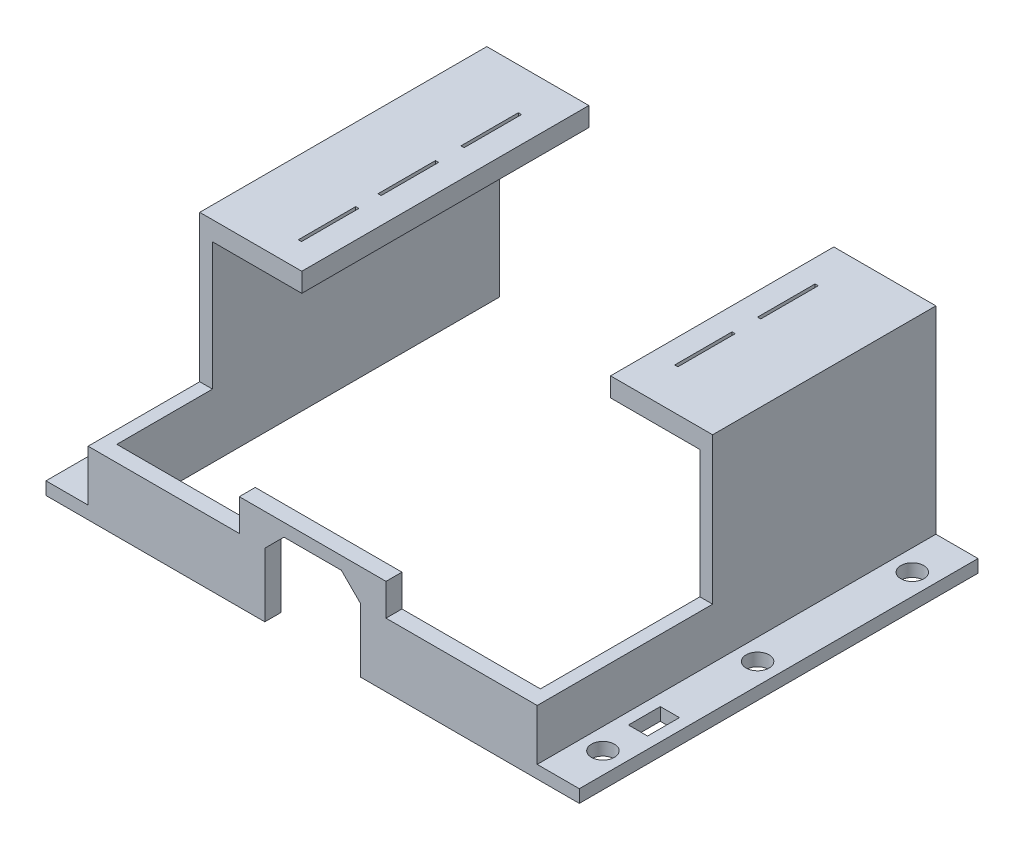
SolidWorks part; units mm, degrees
ref_plane "前视基准面" through (0, 0, 0) normal (0, 0, 1) x (1, 0, 0)
ref_plane "上视基准面" through (0, 0, 0) normal (0, 1, 0) x (1, 0, 0)
ref_plane "右视基准面" through (0, 0, 0) normal (1, 0, 0) x (0, 0, -1)
sketch "Sketch1" plane through (0, 0, 0) normal (0, 1, 0) x (1, 0, 0)
  line L1 (0, 0) -> (70.4, 0)
  line L2 (0, 0) -> (0, 2)
  line L3 (0, 2) -> (70.4, 2)
  line L4 (70.4, 0) -> (70.4, 2)
  dimension "D1" = 70.4
  dimension "D2" = 2
extrude "Boss-Extrude2" add sketch "Sketch1" along normal blind 10
sketch "Sketch2" plane through (0, 10, 0) normal (0, 1, 0) x (1, 0, 0)
  line L1 (0, 2) -> (2, 2)
  line L2 (0, 2) -> (0, 57)
  line L3 (0, 57) -> (2, 57)
  line L4 (2, 2) -> (2, 57)
  line L5 (70.4, 2) -> (68.4, 2)
  line L6 (70.4, 2) -> (70.4, 57)
  line L7 (70.4, 57) -> (68.4, 57)
  line L8 (68.4, 2) -> (68.4, 57)
  dimension "D1" = 55
  dimension "D2" = 2
  dimension "D3" = 2
extrude "Boss-Extrude3" add sketch "Sketch2" against normal blind 10
sketch "Sketch3" plane through (0, 0, 0) normal (0, 0, 1) x (1, 0, 0)
  line L0 (35.2, 0) -> (35.2, 21.6902) construction
  line L1 (0, 0) -> (70.4, 0) construction
  line L2 (0, 10) -> (70.4, 10) construction
  line L3 (25.7, 10) -> (44.7, 10)
  line L4 (25.7, 10) -> (25.7, 13)
  line L5 (25.7, 13) -> (44.7, 13)
  line L6 (44.7, 10) -> (44.7, 13)
  dimension "D1" = 9.5
  dimension "D2" = 9.5
  dimension "D3" = 3
extrude "Boss-Extrude4" add sketch "Sketch3" against normal blind 2
sketch "Sketch4" plane through (0, 0, 0) normal (0, 0, 1) x (1, 0, 0)
  line L0 (35.2, 0) -> (35.2, 21.4055) construction
  line L1 (0, 0) -> (70.4, 0) construction
  line L3 (27.7, 0) -> (42.7, 0)
  line L4 (27.7, 0) -> (27.7, 10)
  line L5 (27.7, 10) -> (42.7, 10)
  line L6 (42.7, 0) -> (42.7, 10)
  dimension "D1" = 10
  dimension "D2" = 7.5
  dimension "D3" = 7.5
extrude "Cut-Extrude2" cut sketch "Sketch4" against normal blind 2
sketch "Sketch5" plane through (25.7, 0, 0) normal (-1, 0, 0) x (0, 0, 1)
  line L1 (-2, 13) -> (0, 13)
  line L2 (-2, 13) -> (-2, 10)
  line L3 (-2, 10) -> (0, 10)
  line L4 (0, 13) -> (0, 10)
extrude "Boss-Extrude5" add sketch "Sketch5" along normal blind 1
sketch "Sketch6" plane through (44.7, 0, 0) normal (1, 0, 0) x (0, 0, -1)
  line L1 (0, 13) -> (2, 13)
  line L2 (0, 13) -> (0, 10)
  line L3 (0, 10) -> (2, 10)
  line L4 (2, 13) -> (2, 10)
extrude "Boss-Extrude6" add sketch "Sketch6" along normal blind 1
sketch "Sketch7" plane through (0, 0, 0) normal (-1, 0, 0) x (0, 0, 1)
  line L0 (0, 10) -> (0, 0) construction
  line L1 (-57, 0) -> (0, 0)
  line L2 (-57, 0) -> (-57, 2)
  line L3 (-57, 2) -> (0, 2)
  line L4 (0, 0) -> (0, 2)
  dimension "D1" = 2
extrude "Boss-Extrude7" add sketch "Sketch7" along normal blind 6.6
sketch "Sketch8" plane through (70.4, 0, 0) normal (1, 0, 0) x (0, 0, -1)
  line L0 (57, 0) -> (57, 10) construction
  line L1 (0, 0) -> (57, 0)
  line L2 (0, 0) -> (0, 2)
  line L3 (0, 2) -> (57, 2)
  line L4 (57, 0) -> (57, 2)
  dimension "D1" = 2
extrude "Boss-Extrude8" add sketch "Sketch8" along normal blind 6.6
sketch "Sketch10" plane through (0, 0, -57) normal (0, 0, -1) x (-1, 0, 0)
  line L0 (-2, 10) -> (-2, 0)
  line L1 (-2, 0) -> (6.6, 0)
  line L2 (6.6, 0) -> (6.6, 2)
  line L3 (6.6, 2) -> (0, 2)
  line L4 (0, 2) -> (0, 10)
  line L5 (0, 10) -> (-2, 10)
  line L6 (-77, 0) -> (-68.4, 0)
  line L7 (-68.4, 0) -> (-68.4, 10)
  line L8 (-68.4, 10) -> (-70.4, 10)
  line L9 (-70.4, 10) -> (-70.4, 2)
  line L10 (-70.4, 2) -> (-77, 2)
  line L11 (-77, 2) -> (-77, 0)
extrude "Boss-Extrude9" add sketch "Sketch10" along normal blind 5
sketch "Sketch12" plane through (0, 10, 0) normal (0, 1, 0) x (1, 0, 0)
  line L0 (0, 0) -> (0, 62) construction
  line L1 (0, 57) -> (2, 57)
  line L2 (0, 57) -> (0, 17)
  line L3 (0, 17) -> (2, 17)
  line L4 (2, 57) -> (2, 17)
  line L5 (2, 2) -> (2, 62) construction
  line L6 (0, 62) -> (2, 62) construction
  line L7 (68.4, 62) -> (68.4, 2) construction
  line L8 (68.4, 57) -> (70.4, 57)
  line L9 (68.4, 57) -> (68.4, 27)
  line L10 (68.4, 27) -> (70.4, 27)
  line L11 (70.4, 57) -> (70.4, 27)
  line L12 (70.4, 62) -> (70.4, 0) construction
  line L13 (68.4, 62) -> (70.4, 62) construction
  line L15 (2, 62) -> (0, 62)
  line L16 (2, 62) -> (2, 57)
  line L17 (2, 57) -> (0, 57)
  line L18 (0, 62) -> (0, 57)
  line L19 (70.4, 62) -> (68.4, 62)
  line L20 (70.4, 62) -> (70.4, 57)
  line L21 (70.4, 57) -> (68.4, 57)
  line L22 (68.4, 62) -> (68.4, 57)
  line M4 (2, 2) -> (2, 62)
  line M5 (2, 62) -> (0, 62)
  line M6 (0, 62) -> (0, 0)
  dimension "D1" = 5
  dimension "D2" = 40
  dimension "D3" = 5
  dimension "D4" = 30
extrude "Boss-Extrude10" add sketch "Sketch12" along normal blind 20 contours L1 M6 M4 M5 | L3 L1 M6 M4 | L11 L8 L9 L10 | L19 L22 L8 L20
sketch "Sketch13" plane through (0, 30, 0) normal (0, 1, 0) x (1, 0, 0)
  line L0 (35.2, 2) -> (35.2, 63.9637) construction
  line L1 (45.7, 2) -> (24.7, 2) construction
  line L2 (0, 17) -> (35.2, 17)
  line L3 (35.2, 17) -> (35.2, 27)
  line L4 (35.2, 27) -> (70.4, 27)
  line L5 (70.4, 27) -> (70.4, 62)
  line L6 (70.4, 62) -> (0, 62)
  line L7 (0, 62) -> (0, 17)
extrude "Boss-Extrude11" add sketch "Sketch13" along normal blind 3
sketch "Sketch14" plane through (0, 33, 0) normal (0, 1, 0) x (1, 0, 0)
  line L0 (35.2, 62) -> (35.2, 11.7147) construction
  line L1 (70.4, 62) -> (0, 62) construction
  line L2 (10.2, 62) -> (10.2, 11.7147) construction
  line L3 (60.2, 62) -> (60.2, 11.7147) construction
  line L4 (10.2, 57) -> (60.2, 57) construction
  line L5 (11.7, 57) -> (11.7, 17) construction
  line L6 (0, 17) -> (35.2, 17) construction
  line L7 (58.2, 57) -> (58.2, 27) construction
  line L8 (35.2, 27) -> (70.4, 27) construction
  line L10 (11.45, 55.5) -> (11.95, 55.5)
  line L11 (11.45, 55.5) -> (11.45, 46.5)
  line L12 (11.45, 46.5) -> (11.95, 46.5)
  line L13 (11.95, 55.5) -> (11.95, 46.5)
  line L14 (11.45, 42.5) -> (11.95, 42.5)
  line L15 (11.45, 42.5) -> (11.45, 33.5)
  line L16 (11.45, 33.5) -> (11.95, 33.5)
  line L17 (11.95, 42.5) -> (11.95, 33.5)
  line L18 (11.45, 30) -> (11.95, 30)
  line L19 (11.45, 30) -> (11.45, 21)
  line L20 (11.45, 21) -> (11.95, 21)
  line L21 (11.95, 30) -> (11.95, 21)
  line L22 (57.95, 55.5) -> (58.45, 55.5)
  line L23 (57.95, 55.5) -> (57.95, 46.5)
  line L24 (57.95, 46.5) -> (58.45, 46.5)
  line L25 (58.45, 55.5) -> (58.45, 46.5)
  line L26 (57.95, 42.5) -> (58.45, 42.5)
  line L27 (57.95, 42.5) -> (57.95, 33.5)
  line L28 (57.95, 33.5) -> (58.45, 33.5)
  line L29 (58.45, 42.5) -> (58.45, 33.5)
  dimension "D1" = 25
  dimension "D2" = 25
  dimension "D3" = 5
  dimension "D4" = 1.5
  dimension "D5" = 2
  dimension "D6" = 0.5
  dimension "D7" = 0.25
  dimension "D8" = 1.5
  dimension "D9" = 9
  dimension "D10" = 4
  dimension "D11" = 9
  dimension "D12" = 9
  dimension "D13" = 3.5
  dimension "D14" = 1.5
  dimension "D15" = 0.25
  dimension "D16" = 0.25
  dimension "D17" = 9
  dimension "D18" = 4
extrude "Cut-Extrude3" cut sketch "Sketch14" against normal blind 3
sketch "Sketch15" plane through (0, 33, 0) normal (0, 1, 0) x (1, 0, 0)
  line L0 (70.4, 62) -> (0, 62) construction
  line L1 (16, 62) -> (54.4, 62)
  line L2 (16, 62) -> (16, 17)
  line L3 (16, 17) -> (54.4, 17)
  line L4 (54.4, 62) -> (54.4, 17)
  line L5 (0, 62) -> (0, 17) construction
  line L6 (70.4, 62) -> (70.4, 0) construction
  dimension "D1" = 16
  dimension "D2" = 16
extrude "Cut-Extrude4" cut sketch "Sketch15" against normal blind 3
sketch "Sketch16" plane through (0, 0, 0) normal (0, 0, 1) x (1, 0, 0)
  line L0 (-6.6, 0) -> (27.7, 0)
  line L1 (27.7, 0) -> (27.7, 10)
  line L2 (27.7, 10) -> (42.7, 10)
  line L3 (42.7, 10) -> (42.7, 0)
  line L4 (42.7, 0) -> (77, 0)
  line L5 (77, 0) -> (77, 2)
  line L6 (77, 2) -> (70.4, 2)
  line L7 (70.4, 2) -> (70.4, 10)
  line L8 (70.4, 10) -> (45.7, 10)
  line L9 (45.7, 10) -> (45.7, 13)
  line L10 (45.7, 13) -> (24.7, 13)
  line L11 (24.7, 13) -> (24.7, 10)
  line L12 (24.7, 10) -> (0, 10)
  line L13 (0, 10) -> (0, 2)
  line L14 (0, 2) -> (-6.6, 2)
  line L15 (-6.6, 2) -> (-6.6, 0)
extrude "Boss-Extrude12" add sketch "Sketch16" along normal blind 0.5
sketch "Sketch17" plane through (0, 2, 0) normal (0, 1, 0) x (1, 0, 0)
  line L0 (-3.3, -0.5) -> (-3.3, 64.6995) construction
  line L1 (0, -0.5) -> (-6.6, -0.5) construction
  line L2 (73.7, -0.5) -> (73.7, 65.8086) construction
  line L3 (77, -0.5) -> (70.4, -0.5) construction
  line L4 (-6.6, 62) -> (0, 62) construction
  line L5 (70.4, 62) -> (77, 62) construction
  line L6 (0, 17) -> (16, 17) construction
  line L7 (-4.8, 17) -> (-1.8, 17)
  line L8 (-4.8, 17) -> (-4.8, 12)
  line L9 (-4.8, 12) -> (-1.8, 12)
  line L10 (-1.8, 17) -> (-1.8, 12)
  line L12 (72.2, 17) -> (75.2, 17)
  line L13 (72.2, 17) -> (72.2, 12)
  line L14 (72.2, 12) -> (75.2, 12)
  line L15 (75.2, 17) -> (75.2, 12)
  circle A0 centre (-3.3, 55) radius 1.8
  circle A1 centre (73.7, 55) radius 1.8
  circle A2 centre (-3.3, 6.5) radius 1.8
  circle A3 centre (73.7, 6.5) radius 1.8
  circle A4 centre (-3.3, 30.75) radius 1.8
  circle A5 centre (73.7, 30.75) radius 1.8
  dimension "D1" = 3.6
  dimension "D2" = 3.6
  dimension "D3" = 3.6
  dimension "D4" = 3.6
  dimension "D9" = 3.6
  dimension "D10" = 3.6
  dimension "D5" = 7
  dimension "D6" = 7
  dimension "D7" = 7
  dimension "D8" = 7
  dimension "D11" = 1.5
  dimension "D12" = 1.5
  dimension "D13" = 5
  dimension "D14" = 0
  dimension "D15" = 1.5
  dimension "D16" = 1.5
extrude "Cut-Extrude6" cut sketch "Sketch17" against normal blind 3
sketch "Sketch18" plane through (24.7, 0, 0) normal (-1, 0, 0) x (0, 0, 1)
  line L1 (0.5, 13) -> (-2, 13)
  line L2 (0.5, 13) -> (0.5, 10)
  line L3 (0.5, 10) -> (-2, 10)
  line L4 (-2, 13) -> (-2, 10)
extrude "Boss-Extrude13" add sketch "Sketch18" along normal blind 1
sketch "Sketch19" plane through (45.7, 0, 0) normal (1, 0, 0) x (0, 0, -1)
  line L1 (2, 13) -> (-0.5, 13)
  line L2 (2, 13) -> (2, 10)
  line L3 (2, 10) -> (-0.5, 10)
  line L4 (-0.5, 13) -> (-0.5, 10)
extrude "Boss-Extrude14" add sketch "Sketch19" along normal blind 1
sketch "Sketch20" plane through (0, 13, 0) normal (0, 1, 0) x (1, 0, 0)
  line L1 (23.7, -0.5) -> (46.7, -0.5)
  line L2 (23.7, -0.5) -> (23.7, 2)
  line L3 (23.7, 2) -> (46.7, 2)
  line L4 (46.7, -0.5) -> (46.7, 2)
extrude "Boss-Extrude15" add sketch "Sketch20" along normal blind 2
sketch "Sketch21" plane through (0, 0, 0.5) normal (0, 0, 1) x (1, 0, 0)
  line L0 (27.7, 10) -> (30.7, 13)
  line L1 (30.7, 13) -> (39.7, 13)
  line L2 (39.7, 13) -> (42.7, 10)
  line L3 (42.7, 10) -> (27.7, 10)
  line L4 (23.7, 15) -> (46.7, 15) construction
  dimension "D1" = 2
  dimension "D2" = 45
  dimension "D3" = 45
extrude "Cut-Extrude8" cut sketch "Sketch21" against normal blind 3
